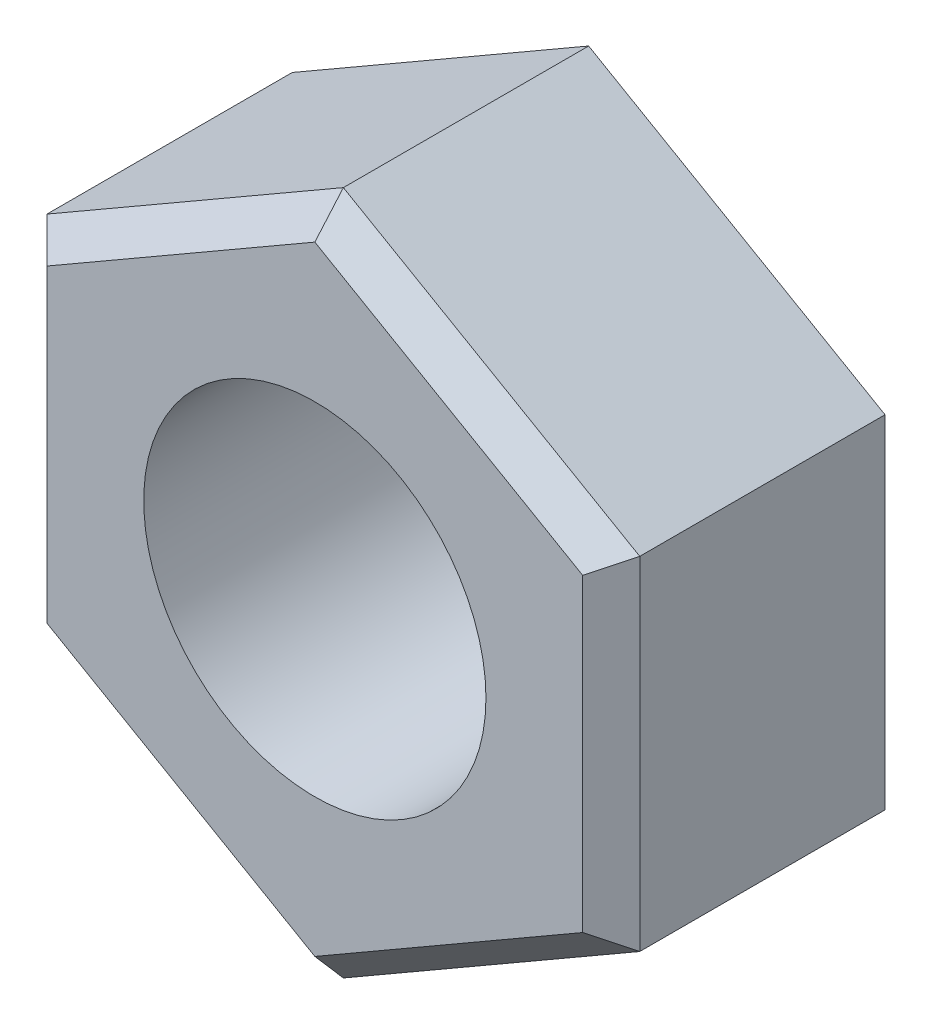
SolidWorks part; units mm, degrees
ref_plane "Plan de face" through (0, 0, 0) normal (0, 0, 1) x (1, 0, 0)
ref_plane "Plan de dessus" through (0, 0, 0) normal (0, 1, 0) x (1, 0, 0)
ref_plane "Plan de droite" through (0, 0, 0) normal (1, 0, 0) x (0, 0, -1)
sketch "Esquisse1" plane through (0, 0, 0) normal (0, 0, 1) x (1, 0, 0)
  line L1 (0, -3) -> (2.5981, -1.5)
  line L2 (2.5981, -1.5) -> (2.5981, 1.5)
  line L3 (2.5981, 1.5) -> (0, 3)
  line L4 (0, 3) -> (-2.5981, 1.5)
  line L5 (-2.5981, 1.5) -> (-2.5981, -1.5)
  line L6 (-2.5981, -1.5) -> (0, -3)
  circle A0 centre (0, 0) radius 2.5981 construction
  circle A1 centre (0, 0) radius 1.5
  dimension "D2" = 3
  dimension "D1" = 6
extrude "Boss.-Extru.1" add sketch "Esquisse1" along normal blind 2.4
chamfer "Chanfrein1" distance 0.25 angle 45 6 edges at (1.299, 2.25, 2.4) (-1.299, 2.25, 2.4) (-2.5981, 0, 2.4) (-1.299, -2.25, 2.4) (2.5981, 0, 2.4) (1.299, -2.25, 2.4)
